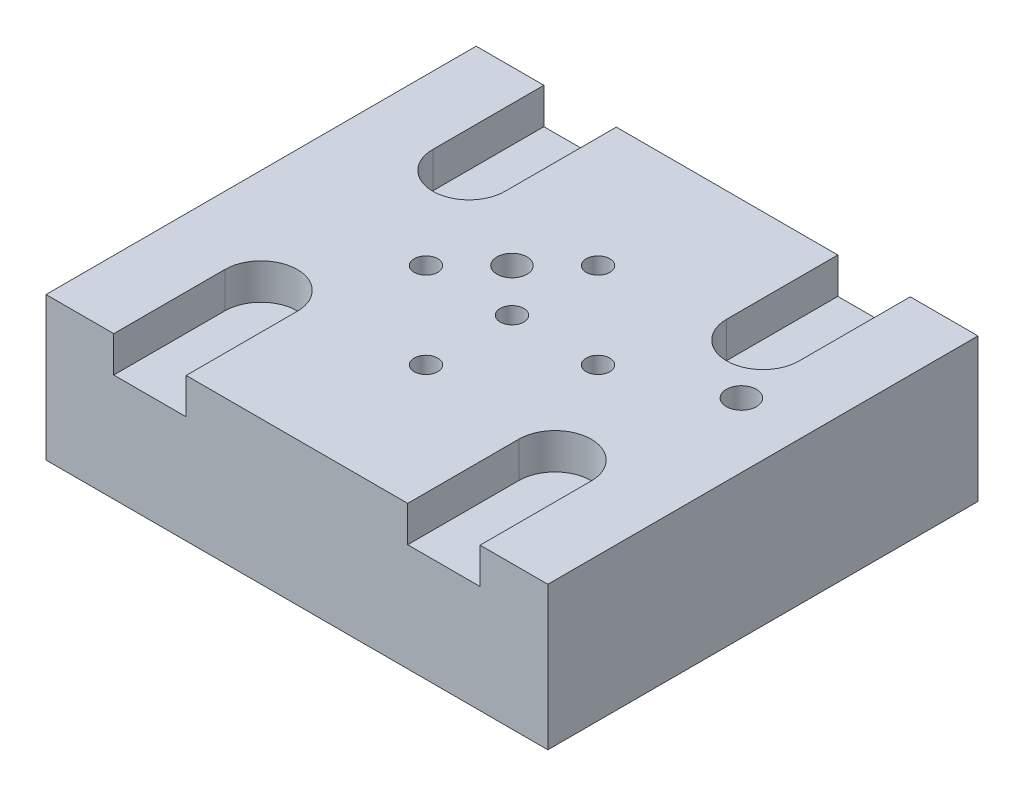
SolidWorks part; units mm, degrees
ref_plane "Front Plane" through (0, 0, 0) normal (0, 0, 1) x (1, 0, 0)
ref_plane "Top Plane" through (0, 0, 0) normal (0, 1, 0) x (1, 0, 0)
ref_plane "Right Plane" through (0, 0, 0) normal (1, 0, 0) x (0, 0, -1)
sketch "Sketch3" plane through (0, 0, 0) normal (0, 1, 0) x (1, 0, 0)
  line L1 (0, 0) -> (70, 0)
  line L2 (0, 0) -> (0, -60)
  line L3 (0, -60) -> (70, -60)
  line L4 (70, 0) -> (70, -60)
  dimension "D1" = 70
  dimension "D2" = 60
extrude "Boss-Extrude3" add sketch "Sketch3" along normal blind 20
sketch "Sketch4" plane through (0, 20, 0) normal (0, 1, 0) x (1, 0, 0)
  line L0 (35, 0) -> (35, -60) construction
  line L1 (70, 0) -> (0, 0) construction
  line L2 (0, -60) -> (70, -60) construction
  line L3 (0, -30) -> (70, -30) construction
  line L4 (0, 0) -> (0, -60) construction
  line L5 (70, -60) -> (70, 0) construction
  line L6 (21.35, -30) -> (21.35, 0) construction
  line L7 (0, 0) -> (70, 0) construction
  line L8 (24.65, -30) -> (24.65, 0) construction
  line L9 (45.35, -30) -> (45.35, 0) construction
  line L10 (48.65, -30) -> (48.65, 0) construction
  circle A0 centre (35, -30) radius 1.65
  circle A1 centre (35, -18) radius 1.65
  circle A2 centre (47, -30) radius 1.65
  circle A3 centre (35, -42) radius 1.65
  circle A4 centre (23, -30) radius 1.65
  dimension "D1" = 3.3
  dimension "D2" = 12
  dimension "D3" = 12
  dimension "D4" = 12
  dimension "D5" = 12
extrude "Cut-Extrude1" cut sketch "Sketch4" against normal through all
sketch "Sketch6" plane through (0, 0, 0) normal (0, -1, 0) x (1, 0, 0)
  line L0 (70, 30) -> (0, 30) construction
  line L1 (55, 24) -> (35, 24) construction
  line L2 (67, 24) -> (70, 24) construction
  line L3 (70, 60) -> (70, 0) construction
  line L4 (0, 0) -> (0, 60) construction
  line L5 (29, 24) -> (29, 0) construction
  line L6 (70, 0) -> (0, 0) construction
  line L7 (61, 24) -> (61, 0) construction
  line L8 (35, 24) -> (35, 0) construction
  line L9 (55, 24) -> (55, 0) construction
  line L10 (23, 24) -> (23, 0) construction
  line L11 (67, 24) -> (67, 0) construction
  line L12 (58.9, 24) -> (58.9, 0) construction
  line L13 (63.1, 24) -> (63.1, 0) construction
  line L14 (31.1, 24) -> (31.1, 0) construction
  line L15 (26.9, 24) -> (26.9, 0) construction
  line L16 (35, 0) -> (35, 60) construction
  line L17 (34.9322, 16.3514) -> (34.9322, 0) construction
  circle A2 centre (61, 24) radius 6 construction
  circle A3 centre (29, 24) radius 6 construction
  circle A4 centre (61, 24) radius 2.1
  circle A5 centre (29, 24) radius 2.1
  circle A6 centre (35, 18) radius 1.65 construction
  point P37 (56.5219, 24.5)
  point P39 (25.6774, 24.5)
  dimension "D1" = 12
  dimension "D2" = 20
  dimension "D3" = 4.2
extrude "Cut-Extrude2" cut sketch "Sketch6" against normal through all contours A4 | A5
sketch "Sketch9" plane through (0, 0, 0) normal (0, 0, -1) x (-1, 0, 0)
  line L0 (-29, 0) -> (-29, 20) construction
  line L1 (-70, 20) -> (0, 20) construction
  line L2 (-61, 0) -> (-61, 20) construction
  line L3 (-67, 0) -> (-55, 0) construction
  line L4 (-23, 0) -> (-23, 20) construction
  line L5 (-35, 0) -> (-35, 20) construction
  line L6 (-55, 0) -> (-55, 20) construction
  line L7 (-67, 0) -> (-67, 20) construction
  line L8 (-58.9, 0) -> (-58.9, 20) construction
  line L9 (-63.1, 0) -> (-63.1, 20) construction
  line L10 (-31.1, 0) -> (-31.1, 20) construction
  line L11 (-26.9, 0) -> (-26.9, 20) construction
  line L12 (-58.9, 7.5) -> (-56.45, 7.5) construction
  line L13 (-53.2, 10.75) -> (-53.2, 20) construction
  line L14 (-13.4822, 7.5) -> (0, 7.5) construction
  line L15 (-19.9822, 7.5) -> (-21.35, 7.5) construction
  line L16 (-16.7322, 20) -> (-16.7322, 10.75) construction
  line L17 (0, 20) -> (0, 0) construction
  line L18 (-34.9322, 0) -> (-34.9322, 20) construction
  line L19 (-34.9322, 0) -> (-34.9322, 20) construction
  line L20 (-49.95, 7.5) -> (-34.9322, 7.5) construction
  line L21 (-21.35, 20) -> (-21.35, 0) construction
  line L22 (0, 0) -> (-70, 0) construction
  line L23 (-24.65, 20) -> (-24.65, 0) construction
  line L24 (-45.35, 20) -> (-45.35, 0) construction
  line L25 (-48.65, 20) -> (-48.65, 0) construction
  line L26 (0, 7.5) -> (0, 20) construction
  circle A0 centre (-53.2, 7.5) radius 3.25
  circle A1 centre (-16.7322, 7.5) radius 3.25
  dimension "D1" = 6.5
  dimension "D2" = 18.2
  dimension "D3" = 18.2
  dimension "D4" = 12.5
extrude "Cut-Extrude3" cut sketch "Sketch9" against normal blind 40.25
sketch "Sketch11" plane through (0, 0, 0) normal (0, -1, 0) x (1, 0, 0)
  line L0 (70, 30) -> (0, 30) construction
  circle A0 centre (23, 30) radius 3
  circle A1 centre (35, 42) radius 3
  circle A2 centre (35, 30) radius 3
  circle A3 centre (35, 18) radius 3
  circle A4 centre (47, 30) radius 3
  circle M3 centre (35, 18) radius 1.65
  circle M4 centre (47, 30) radius 1.65
  circle M5 centre (35, 42) radius 1.65
  circle M6 centre (23, 30) radius 1.65
  circle M7 centre (35, 30) radius 1.65
  dimension "D1" = 6
extrude "Cut-Extrude4" cut sketch "Sketch11" against normal blind 3 contours A3 M3 | A2 M7 | A4 M4 | A0 M6 | A1 M5 | M5 | M6 | M7 | M4 | M3
chamfer "Chamfer1" distance 0.8 angle 45 2 edges at (49.95, 7.5, 0) (13.4822, 7.5, 0)
sketch "Sketch12" plane through (0, 20, 0) normal (0, 1, 0) x (1, 0, 0)
  line L0 (35, -60.1049) -> (14.5, -60.1049) construction
  line L1 (35, 0.1049) -> (35, -60.1049) construction
  line L2 (14.5, -60.1049) -> (14.5, -44.5) construction
  line L3 (9.45, -60.1049) -> (9.45, -44.5)
  line L4 (19.55, -60.1049) -> (19.55, -44.5)
  line L5 (70, -30) -> (0, -30) construction
  line L6 (35, 0) -> (35, -60) construction
  line L7 (35, 0.1049) -> (14.5, 0.1049) construction
  line L8 (55.5, -60.1049) -> (55.5, -44.5) construction
  line L9 (60.55, -60.1049) -> (60.55, -44.5)
  line L10 (50.45, -60.1049) -> (50.45, -44.5)
  line L11 (55.5, 0.1049) -> (55.5, -15.5) construction
  line L12 (60.55, 0.1049) -> (60.55, -15.5)
  line L13 (50.45, 0.1049) -> (50.45, -15.5)
  line L14 (14.5, 0.1049) -> (14.5, -15.5) construction
  line L15 (9.45, 0.1049) -> (9.45, -15.5)
  line L16 (19.55, 0.1049) -> (19.55, -15.5)
  arc A0 (9.45, -60.1049) -> (19.55, -60.1049) centre (14.5, -60.1049) ccw
  arc A1 (19.55, -44.5) -> (9.45, -44.5) centre (14.5, -44.5) ccw
  arc A3 (60.55, -60.1049) -> (50.45, -60.1049) centre (55.5, -60.1049) cw
  arc A4 (50.45, -44.5) -> (60.55, -44.5) centre (55.5, -44.5) cw
  arc A6 (60.55, 0.1049) -> (50.45, 0.1049) centre (55.5, 0.1049) ccw
  arc A7 (50.45, -15.5) -> (60.55, -15.5) centre (55.5, -15.5) ccw
  arc A8 (9.45, 0.1049) -> (19.55, 0.1049) centre (14.5, 0.1049) cw
  arc A9 (19.55, -15.5) -> (9.45, -15.5) centre (14.5, -15.5) cw
  point P0 (14.5, -52.3025)
  point P19 (35, -30)
  point P23 (55.5, -52.3025)
  point P29 (55.5, -7.6975)
  point P36 (14.5, -7.6975)
  dimension "D4" = 5.05
  dimension "D1" = 20.5
extrude "Cut-Extrude5" cut sketch "Sketch12" against normal blind 5
